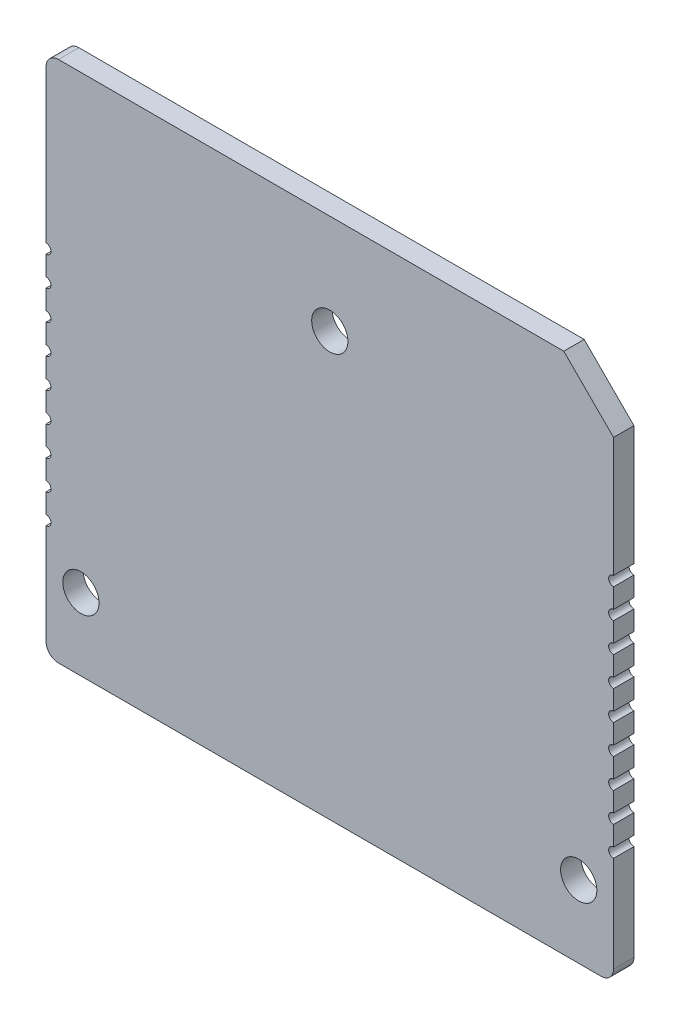
SolidWorks part; units mm, degrees
ref_plane "Front Plane" through (0, 0, 0) normal (0, 0, 1) x (1, 0, 0)
ref_plane "Top Plane" through (0, 0, 0) normal (0, 1, 0) x (1, 0, 0)
ref_plane "Right Plane" through (0, 0, 0) normal (1, 0, 0) x (0, 0, -1)
sketch "Sketch1" plane through (0, 0, 0) normal (0, 0, 1) x (1, 0, 0)
  line L0 (0, 5.75) -> (0, 0.635)
  line L1 (0.635, 0) -> (28.321, 0)
  line L2 (28.956, 0.635) -> (28.956, 5.53)
  line L3 (28.956, 6.03) -> (28.956, 7.03)
  line L4 (28.956, 7.53) -> (28.956, 8.53)
  line L5 (28.956, 9.03) -> (28.956, 10.03)
  line L6 (28.956, 10.53) -> (28.956, 11.53)
  line L7 (28.956, 12.03) -> (28.956, 13.03)
  line L8 (28.956, 13.53) -> (28.956, 14.53)
  line L9 (28.956, 15.03) -> (28.956, 16.03)
  line L10 (28.956, 16.53) -> (28.956, 17.53)
  line L11 (28.956, 18.03) -> (28.956, 24.13)
  line L12 (28.956, 24.13) -> (26.416, 26.67)
  line L13 (26.416, 26.67) -> (0.635, 26.67)
  line L14 (0, 26.035) -> (0, 18.25)
  line L15 (0, 17.75) -> (0, 16.75)
  line L16 (0, 16.25) -> (0, 15.25)
  line L17 (0, 14.75) -> (0, 13.75)
  line L18 (0, 13.25) -> (0, 12.25)
  line L19 (0, 11.75) -> (0, 10.75)
  line L20 (0, 10.25) -> (0, 9.25)
  line L21 (0, 8.75) -> (0, 7.75)
  line L22 (0, 7.25) -> (0, 6.25)
  arc A0 (0, 6.25) -> (0, 5.75) centre (0, 6) cw
  arc A1 (0, 0.635) -> (0.635, 0) centre (0.635, 0.635) ccw
  arc A2 (28.321, 0) -> (28.956, 0.635) centre (28.321, 0.635) ccw
  arc A3 (28.956, 5.53) -> (28.956, 6.03) centre (28.956, 5.78) cw
  arc A4 (28.956, 7.03) -> (28.956, 7.53) centre (28.956, 7.28) cw
  arc A5 (28.956, 8.53) -> (28.956, 9.03) centre (28.956, 8.78) cw
  arc A6 (28.956, 10.03) -> (28.956, 10.53) centre (28.956, 10.28) cw
  arc A7 (28.956, 11.53) -> (28.956, 12.03) centre (28.956, 11.78) cw
  arc A8 (28.956, 13.03) -> (28.956, 13.53) centre (28.956, 13.28) cw
  arc A9 (28.956, 14.53) -> (28.956, 15.03) centre (28.956, 14.78) cw
  arc A10 (28.956, 16.03) -> (28.956, 16.53) centre (28.956, 16.28) cw
  arc A11 (28.956, 17.53) -> (28.956, 18.03) centre (28.956, 17.78) cw
  arc A12 (0.635, 26.67) -> (0, 26.035) centre (0.635, 26.035) ccw
  arc A13 (0, 18.25) -> (0, 17.75) centre (0, 18) cw
  arc A14 (0, 16.75) -> (0, 16.25) centre (0, 16.5) cw
  arc A15 (0, 15.25) -> (0, 14.75) centre (0, 15) cw
  arc A16 (0, 13.75) -> (0, 13.25) centre (0, 13.5) cw
  arc A17 (0, 12.25) -> (0, 11.75) centre (0, 12) cw
  arc A18 (0, 10.75) -> (0, 10.25) centre (0, 10.5) cw
  arc A19 (0, 9.25) -> (0, 8.75) centre (0, 9) cw
  arc A20 (0, 7.75) -> (0, 7.25) centre (0, 7.5) cw
  circle A21 centre (27.178, 3.683) radius 0.925
  circle A22 centre (1.778, 3.683) radius 0.925
  circle A23 centre (14.478, 21.59) radius 0.925
extrude "Boss-Extrude1" add sketch "Sketch1" against normal blind 1.041
